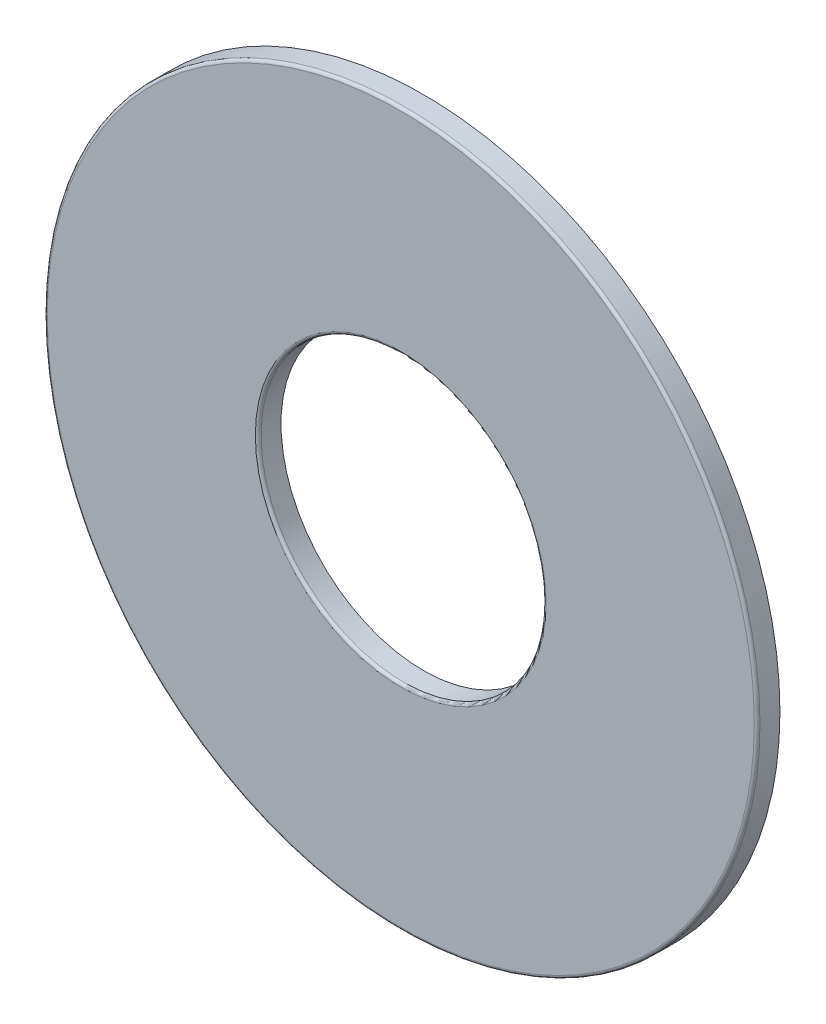
SolidWorks part; units mm, degrees
ref_plane "Front Plane" through (0, 0, 0) normal (0, 0, 1) x (1, 0, 0)
ref_plane "Top Plane" through (0, 0, 0) normal (0, 1, 0) x (1, 0, 0)
ref_plane "Right Plane" through (0, 0, 0) normal (1, 0, 0) x (0, 0, -1)
sketch "Sketch1" plane through (0, 0, 0) normal (0, 0, 1) x (1, 0, 0)
  circle A0 centre (0, 0) radius 5
  circle A1 centre (0, 0) radius 12.5
  dimension "D1" = 10
  dimension "D2" = 25
extrude "Boss-Extrude1" add sketch "Sketch1" along normal blind 0.8
fillet "Fillet1" radius 0.1 2 edges at (12.5, 0, 0.8) (5, 0, 0.8)
